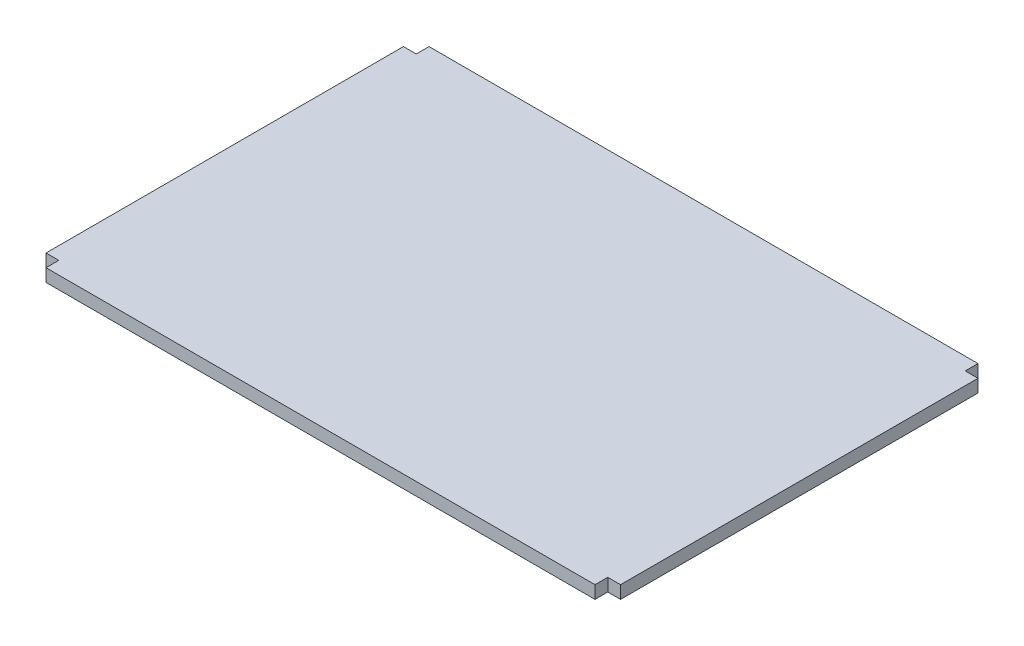
SolidWorks part; units mm, degrees
ref_plane "Front Plane" through (0, 0, 0) normal (0, 0, 1) x (1, 0, 0)
ref_plane "Top Plane" through (0, 0, 0) normal (0, 1, 0) x (1, 0, 0)
ref_plane "Right Plane" through (0, 0, 0) normal (1, 0, 0) x (0, 0, -1)
sketch "Sketch2" plane through (0, 0, 0) normal (0, 1, 0) x (1, 0, 0)
  line L1 (450, 300) -> (-450, 300)
  line L2 (450, 300) -> (450, -300)
  line L3 (450, -300) -> (-450, -300)
  line L4 (-450, 300) -> (-450, -300)
  line L5 (450, 300) -> (-450, -300) construction
  line L6 (450, -300) -> (-450, 300) construction
  point P0 (0, 0)
  dimension "D1" = 900
  dimension "D2" = 600
extrude "Boss-Extrude1" add sketch "Sketch2" along normal blind 20
sketch "Sketch3" plane through (0, 20, 0) normal (0, 1, 0) x (1, 0, 0)
  line L1 (-450, 300) -> (-430, 300)
  line L2 (-450, 300) -> (-450, 280)
  line L3 (-450, 280) -> (-430, 280)
  line L4 (-430, 300) -> (-430, 280)
  dimension "D1" = 20
sketch "Sketch4" plane through (0, 20, 0) normal (0, 1, 0) x (1, 0, 0)
  line L0 (450, 300) -> (-450, 300) construction
  line L1 (450, 300) -> (433.5096, 300)
  line L2 (450, 300) -> (450, 279.8414)
  line L3 (450, 279.8414) -> (433.5096, 279.8414)
  line L4 (433.5096, 300) -> (433.5096, 279.8414)
  line L5 (450, -300) -> (450, 300) construction
extrude "Boss-Extrude3" add sketch "Sketch4" against normal blind 20
sketch "Sketch7" plane through (0, 20, 0) normal (0, 1, 0) x (1, 0, 0)
  line L1 (450, 300) -> (430, 300)
  line L2 (450, 300) -> (450, 280)
  line L3 (450, 280) -> (430, 280)
  line L4 (430, 300) -> (430, 280)
  dimension "D1" = 20
extrude "Cut-Extrude2" cut sketch "Sketch7" against normal blind 20
sketch "Sketch8" plane through (0, 20, 0) normal (0, 1, 0) x (1, 0, 0)
  line L1 (450, -300) -> (430, -300)
  line L2 (450, -300) -> (450, -280)
  line L3 (450, -280) -> (430, -280)
  line L4 (430, -300) -> (430, -280)
  dimension "D1" = 20
extrude "Cut-Extrude3" cut sketch "Sketch8" against normal blind 20
sketch "Sketch10" plane through (0, 20, 0) normal (0, 1, 0) x (1, 0, 0)
  line L1 (-450, 300) -> (-430, 300)
  line L2 (-450, 300) -> (-450, 280)
  line L3 (-450, 280) -> (-430, 280)
  line L4 (-430, 300) -> (-430, 280)
  dimension "D1" = 20
extrude "Cut-Extrude4" cut sketch "Sketch10" against normal blind 20
sketch "Sketch11" plane through (0, 20, 0) normal (0, 1, 0) x (1, 0, 0)
  line L1 (-450, -300) -> (-430, -300)
  line L2 (-450, -300) -> (-450, -280)
  line L3 (-450, -280) -> (-430, -280)
  line L4 (-430, -300) -> (-430, -280)
  dimension "D1" = 20
extrude "Cut-Extrude5" cut sketch "Sketch11" against normal blind 20
sketch "Sketch12" plane through (0, 20, 0) normal (0, 1, 0) x (1, 0, 0)
  line L0 (-430, -280) -> (430, -280)
  line L1 (0, 280) -> (0, -297.2561) construction
  line L2 (-200, -80) -> (200, -80)
  line L3 (-450, 0) -> (450, 0) construction
  line L4 (-450, 280) -> (-450, -280) construction
  line L5 (450, -280) -> (450, 280) construction
  line L6 (-120, -50.8545) -> (120, -50.8545)
  line L7 (-430, 280) -> (430, 280)
  line L8 (-200, 280) -> (-200, -280)
  line L9 (200, 280) -> (200, -409.3128) construction
  line L10 (120, -50.8545) -> (120, 159.1455)
  line L11 (-200, -280) -> (200, -280)
  line L12 (-200, -280) -> (-200, -80)
  line L13 (120, 159.1455) -> (-120, 159.1455)
  line L14 (200, -280) -> (200, -80)
  line L15 (-120, 159.1455) -> (-120, -50.8545)
  line L16 (-130, -60.8545) -> (130, -60.8545)
  line L17 (130, -60.8545) -> (130, 169.1455)
  line L18 (130, 169.1455) -> (-130, 169.1455)
  line L19 (-130, 169.1455) -> (-130, -60.8545)
  line L21 (200, -280) -> (310, -280)
  line L22 (200, -280) -> (200, -190)
  line L23 (200, -190) -> (310, -190)
  line L24 (310, -280) -> (310, -190)
  line L25 (200, -190) -> (310, -190)
  line L26 (200, -190) -> (200, -80)
  line L27 (200, -80) -> (310, -80)
  line L28 (310, -190) -> (310, -80)
  line L29 (-200, -280) -> (-430, -280)
  line L30 (-200, -280) -> (-200, -80)
  line L31 (-200, -80) -> (-430, -80)
  line L32 (-430, -280) -> (-430, -80)
  point P6 (0, 159.1455)
  point P25 (0, 280)
  dimension "D1" = 240
  dimension "D2" = 210
  dimension "D3" = 400
  dimension "D4" = 200
  dimension "D5" = 10
  dimension "D6" = 10
  dimension "D7" = 10
  dimension "D8" = 10
  dimension "D9" = 110
  dimension "D10" = 90
  dimension "D11" = 110
  dimension "D12" = 110
sketch "Sketch13" plane through (0, 20, 0) normal (0, 1, 0) x (1, 0, 0)
  line L0 (130, -80) -> (130, 320.2789)
  line L1 (-200, -80) -> (200, -80) construction
  line L2 (130, -60.8545) -> (130, 169.1455) construction
  line L3 (130, -80) -> (240, -80)
  line L4 (240, -80) -> (240, 30)
  line L5 (240, 30) -> (130, 30)
  line L7 (130, 30) -> (240, 30)
  line L8 (130, 30) -> (130, 140)
  line L9 (130, 140) -> (240, 140)
  line L10 (240, 30) -> (240, 140)
  line L11 (130, 140) -> (240, 140)
  line L12 (130, 140) -> (130, 250)
  line L13 (130, 250) -> (240, 250)
  line L14 (240, 140) -> (240, 250)
  line L15 (-130, 169.1455) -> (-130, -60.8545) construction
  line L16 (-130, -80) -> (-240, -80)
  line L17 (-130, -80) -> (-130, 30)
  line L18 (-130, 30) -> (-240, 30)
  line L19 (-240, -80) -> (-240, 30)
  line L21 (-130, 30) -> (-240, 30)
  line L22 (-130, 30) -> (-130, 140)
  line L23 (-130, 140) -> (-240, 140)
  line L24 (-240, 30) -> (-240, 140)
  line L25 (-130, 140) -> (-240, 140)
  line L26 (-130, 140) -> (-130, 250)
  line L27 (-130, 250) -> (-240, 250)
  line L28 (-240, 140) -> (-240, 250)
  dimension "D1" = 110
  dimension "D2" = 110
  dimension "D3" = 110
  dimension "D4" = 110
  dimension "D5" = 110
  dimension "D6" = 110
  dimension "D7" = 110
